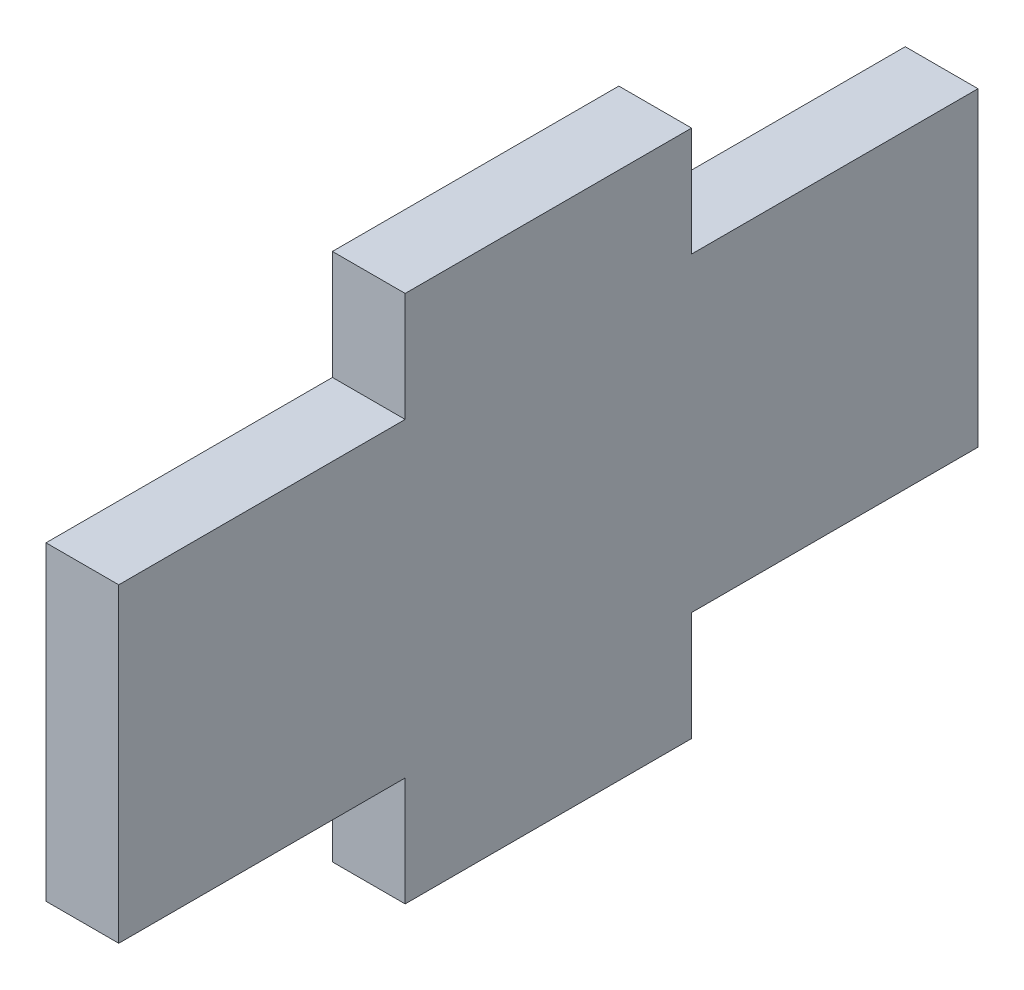
SolidWorks part; units mm, degrees
ref_plane "Front Plane" through (0, 0, 0) normal (0, 0, 1) x (1, 0, 0)
ref_plane "Top Plane" through (0, 0, 0) normal (0, 1, 0) x (1, 0, 0)
ref_plane "Right Plane" through (0, 0, 0) normal (1, 0, 0) x (0, 0, -1)
sketch "Sketch1" plane through (0, 0, 0) normal (1, 0, 0) x (0, 0, -1)
  line L2 (12.5, 23.075) -> (12.5, 13.55)
  line L4 (-12.5, 13.55) -> (-12.5, 23.075)
  line L7 (-37.5, 0) -> (37.5, 0)
  line L8 (-37.5, 0) -> (-37.5, 13.55)
  line L9 (-37.5, 13.55) -> (-12.5, 13.55)
  line L10 (-12.5, 23.075) -> (12.5, 23.075)
  line L11 (12.5, 13.55) -> (37.5, 13.55)
  line L12 (37.5, 13.55) -> (37.5, 0)
  point P2 (0, 0)
  point P9 (-15.1218, 13.55)
  point P12 (0, 23.075)
  dimension "D1" = 75
  dimension "D2" = 9.525
  dimension "D3" = 13.55
  dimension "D4" = 25
extrude "Boss-Extrude1" add sketch "Sketch1" along normal mid plane 6.35
mirror "Mirror1" about plane through (0, 0, 0) normal (0, 1, 0) of "Boss-Extrude1"
